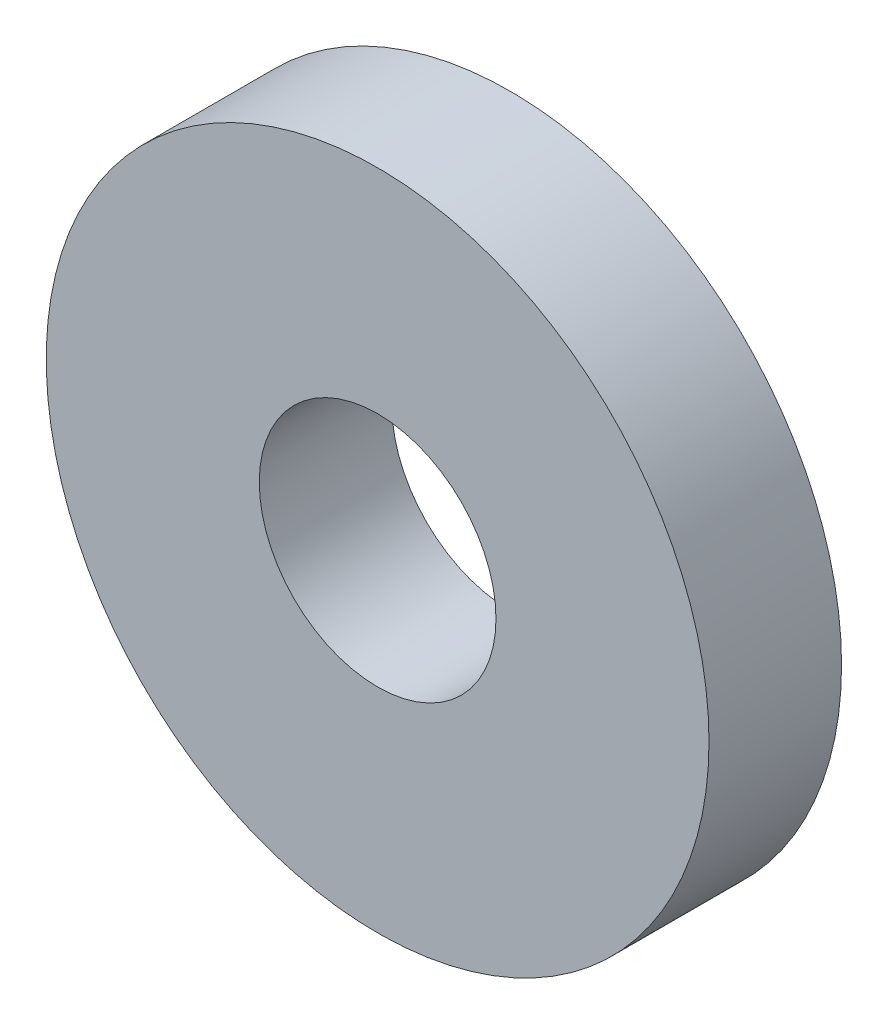
SolidWorks part; units mm, degrees
ref_plane "前基準面" through (0, 0, 0) normal (0, 0, 1) x (1, 0, 0)
ref_plane "上基準面" through (0, 0, 0) normal (0, 1, 0) x (1, 0, 0)
ref_plane "右基準面" through (0, 0, 0) normal (1, 0, 0) x (0, 0, -1)
sketch "草圖1" plane through (0, 0, 0) normal (0, 0, 1) x (1, 0, 0)
  circle A0 centre (0, 0) radius 7
extrude "填料-伸長1" add sketch "草圖1" along normal blind 2.8
sketch "草圖2" plane through (0, 0, 2.8) normal (0, 0, 1) x (1, 0, 0)
  circle A0 centre (0, 0) radius 2.5
extrude "除料-伸長1" cut sketch "草圖2" against normal blind 2.8
